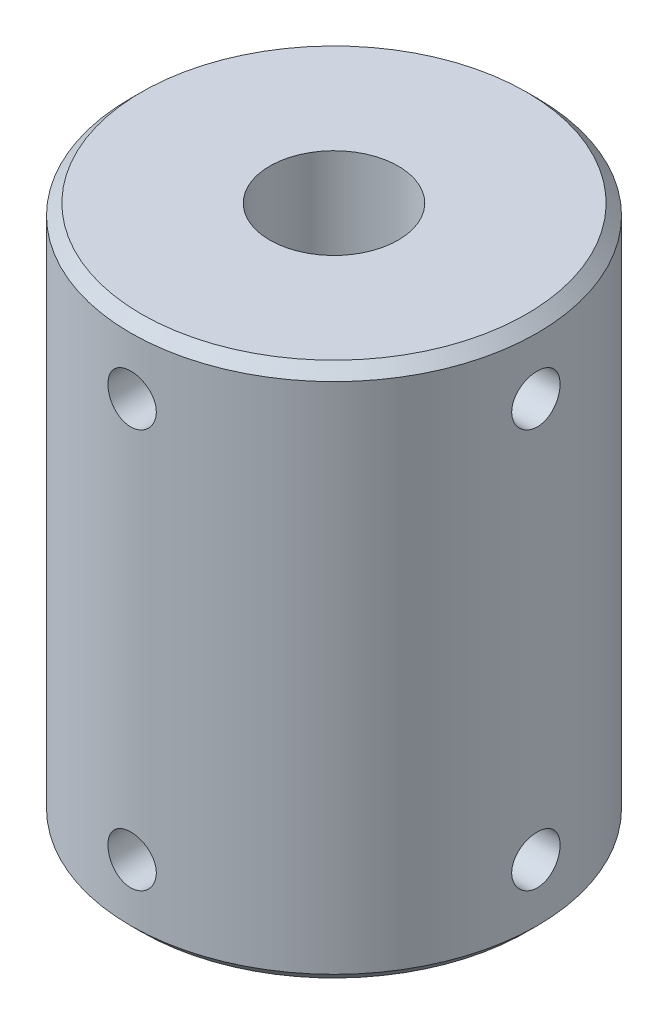
SolidWorks part; units mm, degrees
material "1060 Alloy"
ref_plane "Front" through (0, 0, 0) normal (0, 0, 1) x (1, 0, 0)
ref_plane "Top" through (0, 0, 0) normal (0, 1, 0) x (1, 0, 0)
ref_plane "Right" through (0, 0, 0) normal (1, 0, 0) x (0, 0, -1)
sketch "Sketch1" plane through (0, 0, 0) normal (0, 1, 0) x (1, 0, 0)
  circle A0 centre (0, 0) radius 9.5
  dimension "D1" = 19
extrude "Boss-Extrude1" add sketch "Sketch1" along normal blind 25
chamfer "Chamfer1" distance 0.508 angle 45 2 edges at (0, 0, 9.5) (0, 25, 9.5)
sketch "Sketch2" plane through (0, 25, 0) normal (0, 1, 0) x (1, 0, 0)
  circle A0 centre (0, 0) radius 3
  dimension "D1" = 6
hole_wizard "Ø6.0mm Dowel Hole1" positions "Sketch3" profile "Sketch4" hole size "Ø6.0" standard "ANSI Metric" end condition through all
sketch "Sketch3" plane through (0, 25, 0) normal (0, 1, 0) x (1, 0, 0)
  point P0 (0, 0)
sketch "Sketch4" plane through (0, 25, 0) normal (1, 0, 0) x (0, 0, 1)
  line L0 (0, 0) -> (0, 25)
  line L1 (0, 25) -> (3, 25)
  line L2 (3, 25) -> (3, 0)
  line L5 (3, 0) -> (0, 0)
  line L11 (0, -6.35) -> (0, 107.95) construction
  dimension "Thru Hole Dia." = 6
  dimension "Thru Hole Depth" = 25
sketch "Sketch5" plane through (0, 0, 0) normal (1, 0, 0) x (0, 0, -1)
  line L0 (0, 0) -> (0, 25) construction
  line L1 (3, 25) -> (-3, 25) construction
  circle A0 centre (0, 21.825) radius 1.5
  circle A1 centre (0, 3.175) radius 1.5
  dimension "D2" = 3
  dimension "D1" = 3.175
  dimension "D3" = 3.175
hole_wizard "#4-40 Tapped Hole1" positions "Sketch6" profile "Sketch7" tap size "#4-40" standard "ANSI Inch"
sketch "Sketch6" plane through (0, 0, 0) normal (1, 0, 0) x (0, 0, -1)
  point P0 (0, 21.825)
  point P3 (0, 3.175)
sketch "Sketch7" plane through (0, 21.825, 0) normal (0, 1, 0) x (0, 0, 1)
  line L0 (0, 0) -> (0, 9.5)
  line L1 (0, 9.5) -> (1.1303, 9.5)
  line L2 (1.1303, 9.5) -> (1.1303, 0)
  line L5 (1.1303, 0) -> (0, 0)
  line L11 (0, -6.35) -> (0, 107.95) construction
  dimension "Thru Tap Drill Dia." = 2.2606
  dimension "Thru Tap Drill Depth" = 9.5
cosmetic thread "Hole Thread1" parameters "D2"=2.8448
cosmetic thread "Hole Thread2" parameters "D2"=2.8448
sketch "Sketch8" plane through (0, 0, 0) normal (0, 0, 1) x (1, 0, 0)
  line L0 (0, 1.675) -> (0, 4.675) construction
  line L1 (0, 20.325) -> (0, 23.325) construction
  circle A0 centre (0, 3.175) radius 1.5
  circle A1 centre (0, 21.825) radius 1.5
  dimension "D1" = 3
hole_wizard "#4-40 Tapped Hole2" positions "Sketch9" profile "Sketch10" tap size "#4-40" standard "ANSI Inch"
sketch "Sketch9" plane through (0, 0, 0) normal (0, 0, 1) x (1, 0, 0)
  point P0 (0, 21.825)
  point P3 (0, 3.175)
sketch "Sketch10" plane through (0, 21.825, 0) normal (1, 0, 0) x (0, 1, 0)
  line L0 (0, 0) -> (0, 9.5)
  line L1 (0, 9.5) -> (1.1303, 9.5)
  line L2 (1.1303, 9.5) -> (1.1303, 0)
  line L5 (1.1303, 0) -> (0, 0)
  line L11 (0, -6.35) -> (0, 107.95) construction
  dimension "Thru Tap Drill Dia." = 2.2606
  dimension "Thru Tap Drill Depth" = 9.5
cosmetic thread "Hole Thread3" parameters "D2"=2.8448
cosmetic thread "Hole Thread4" parameters "D2"=2.8448
sketch "Sketch11" plane through (0, 0, 0) normal (0, 0, 1) x (1, 0, 0)
  line L0 (-9.5, 24.492) -> (-9.5, 0.508) construction
  line L1 (-9.5, 18.65) -> (-3.15, 18.65)
  line L2 (-9.5, 18.65) -> (-9.5, 17.761)
  line L3 (-9.5, 17.761) -> (-3.15, 17.761)
  line L4 (-3.15, 18.65) -> (-3.15, 17.761)
  line L6 (8.992, 25) -> (-8.992, 25) construction
  dimension "D1" = 0.889
  dimension "D2" = 6.35
  dimension "D3" = 6.35
equation "\"D3@Sketch5\"=\"D1@Sketch5\""
